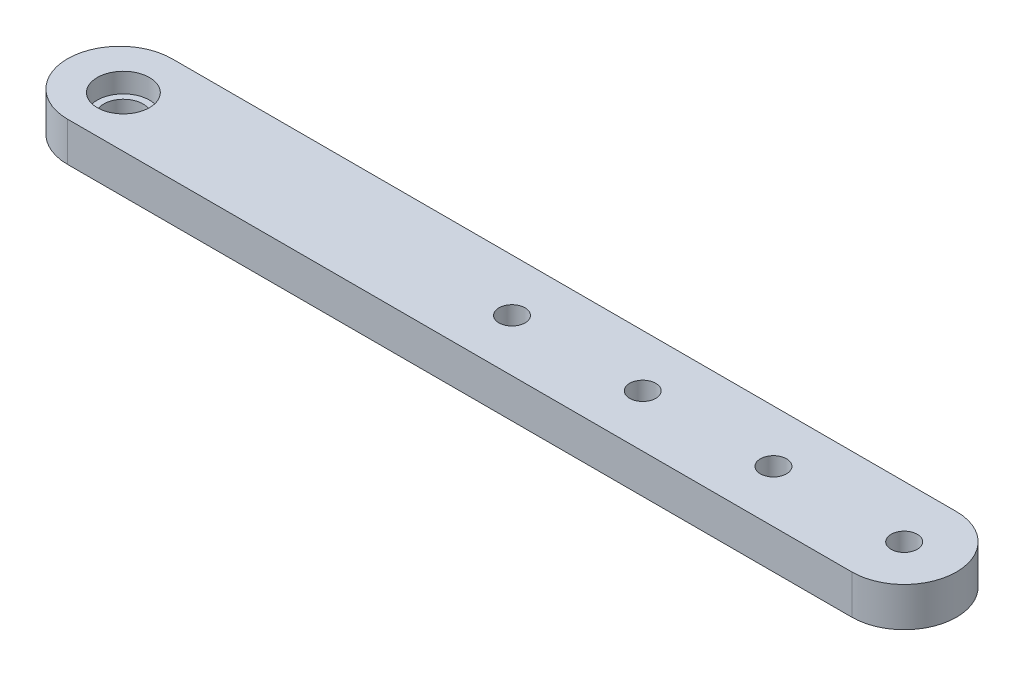
SolidWorks part; units mm, degrees
material "Plain Carbon Steel"
ref_plane "Front Plane" through (0, 0, 0) normal (0, 0, 1) x (1, 0, 0)
ref_plane "Top Plane" through (0, 0, 0) normal (0, 1, 0) x (1, 0, 0)
ref_plane "Right Plane" through (0, 0, 0) normal (1, 0, 0) x (0, 0, -1)
sketch "Sketch1" plane through (0, 0, 0) normal (0, 1, 0) x (1, 0, 0)
  line L0 (-56.2508, 0) -> (60, 0) construction
  line L1 (-60, -8) -> (60, -8)
  line L3 (-60, 8) -> (60, 8)
  line L11 (0, 8) -> (0, -8) construction
  circle A2 centre (-59.2433, -0.2116) radius 3
  circle A3 centre (60, 0) radius 2
  circle A4 centre (20, 0) radius 2
  arc A5 (-60, 8) -> (-60, -8) centre (-60, 0) ccw
  arc A7 (60, -8) -> (60, 8) centre (60, 0) ccw
  circle A8 centre (40, 0) radius 2
  circle A9 centre (0, 0) radius 2
  point P0 (0, 0)
  point P17 (0, 0)
  dimension "D3" = 6
  dimension "D4" = 4
  dimension "D5" = 4
  dimension "D8" = 16
  dimension "D9" = 4
  dimension "D10" = 4
  dimension "D1" = 120
  dimension "D2" = 8
  dimension "D6" = 60
  dimension "D7" = 40
  dimension "D11" = 20
  dimension "D12" = 20
extrude "Boss-Extrude1" add sketch "Sketch1" along normal blind 6
sketch "Sketch3" plane through (0, 6, 0) normal (0, 1, 0) x (1, 0, 0)
  circle A0 centre (-59.2433, -0.2116) radius 4
  dimension "D1" = 8
extrude "Cut-Extrude1" cut sketch "Sketch3" against normal blind 3
